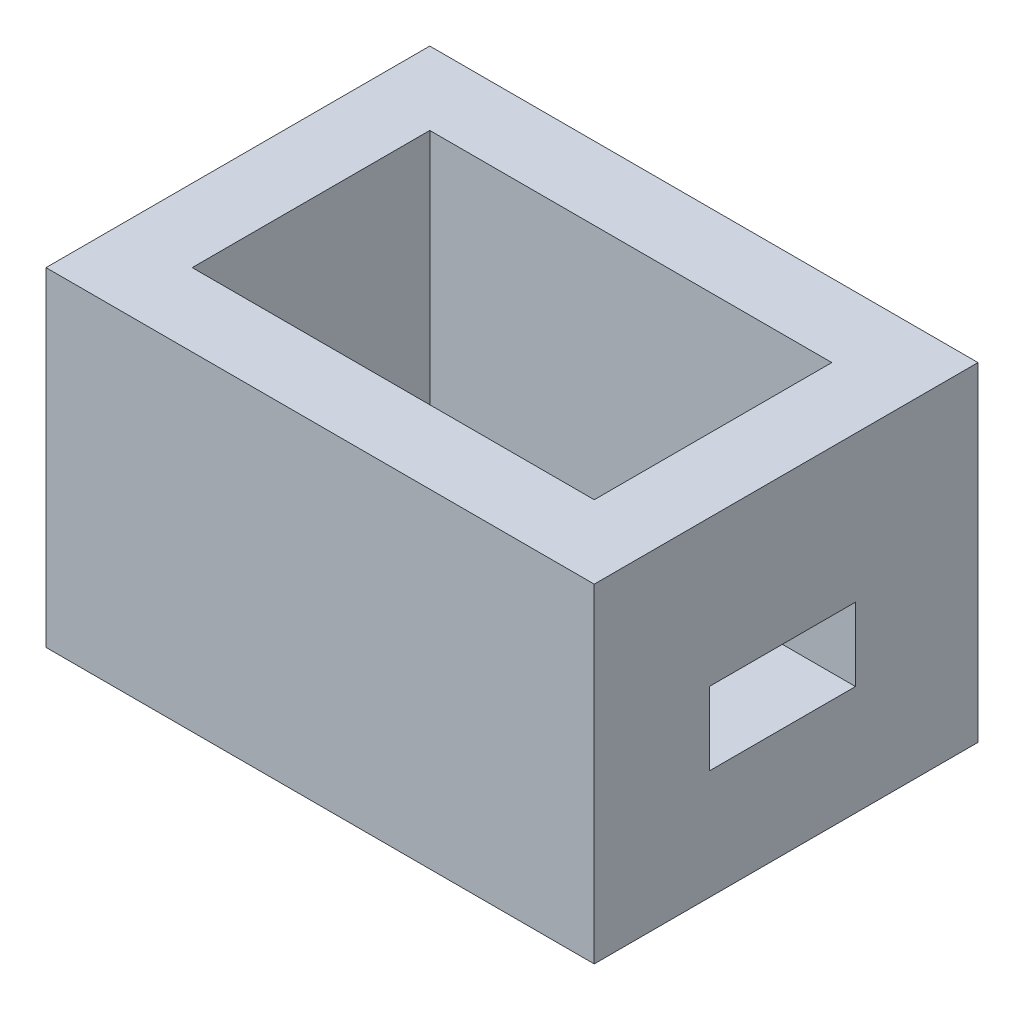
SolidWorks part; units mm, degrees
ref_plane "Front Plane" through (0, 0, 0) normal (0, 0, 1) x (1, 0, 0)
ref_plane "Top Plane" through (0, 0, 0) normal (0, 1, 0) x (1, 0, 0)
ref_plane "Right Plane" through (0, 0, 0) normal (1, 0, 0) x (0, 0, -1)
sketch "Sketch2" plane through (0, 0, 0) normal (0, 1, 0) x (1, 0, 0)
  line L1 (-15, -10.5) -> (15, -10.5)
  line L2 (-15, -10.5) -> (-15, 10.5)
  line L3 (-15, 10.5) -> (15, 10.5)
  line L4 (15, -10.5) -> (15, 10.5)
  line L5 (-15, -10.5) -> (15, 10.5) construction
  line L6 (-15, 10.5) -> (15, -10.5) construction
  point P0 (0, 0)
  dimension "D1" = 30
  dimension "D2" = 21
extrude "Boss-Extrude3" add sketch "Sketch2" along normal blind 18 contours L2 L1 L4 L3
shell "Shell5" thickness 4
sketch "Sketch3" plane through (15, 0, 0) normal (1, 0, 0) x (0, 0, -1)
  line L0 (-10.5, 0) -> (10.5, 0) construction
  line L1 (-4.2054, 6) -> (3.7946, 6)
  line L2 (-4.2054, 6) -> (-4.2054, 10)
  line L3 (-4.2054, 10) -> (3.7946, 10)
  line L4 (3.7946, 6) -> (3.7946, 10)
  line L5 (-4.2054, 6) -> (3.7946, 10) construction
  line L6 (-4.2054, 10) -> (3.7946, 6) construction
  point P0 (-0.2054, 8)
  dimension "D1" = 8
  dimension "D2" = 4
  dimension "D3" = 6
extrude "Cut-Extrude2" cut sketch "Sketch3" against normal blind 21.4 contours L2 L1 L4 L3
